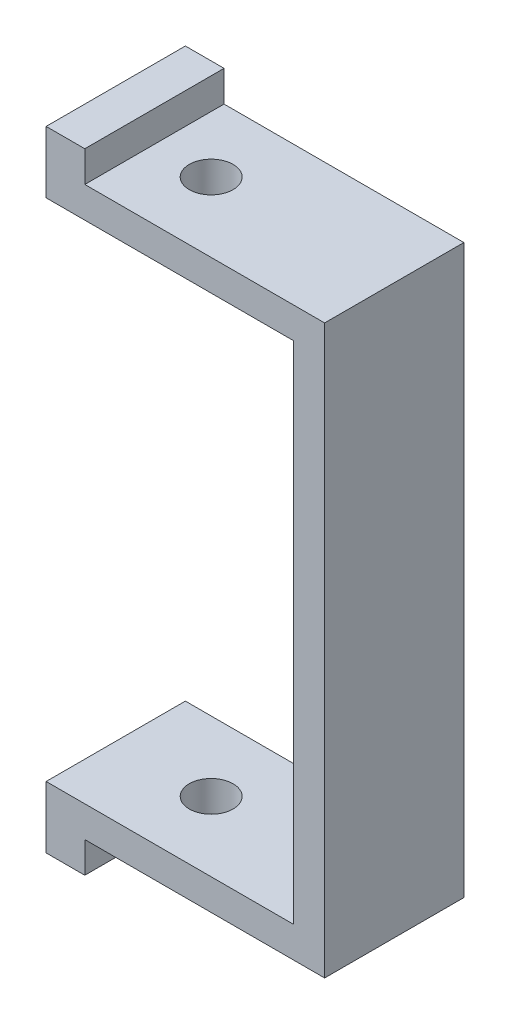
SolidWorks part; units mm, degrees
ref_plane "Alzado" through (0, 0, 0) normal (0, 0, 1) x (1, 0, 0)
ref_plane "Planta" through (0, 0, 0) normal (0, 1, 0) x (1, 0, 0)
ref_plane "Vista lateral" through (0, 0, 0) normal (1, 0, 0) x (0, 0, -1)
sketch "Croquis1" plane through (0, 0, 0) normal (0, 0, 1) x (1, 0, 0)
  line L0 (3.75, 0) -> (27, 0)
  line L1 (27, 0) -> (27, 55)
  line L2 (27, 55) -> (3.75, 55)
  line L3 (0, 3) -> (24, 3)
  line L4 (24, 3) -> (24, 52)
  line L5 (24, 52) -> (0, 52)
  line L6 (0, 55) -> (0, 52)
  line L7 (0, 3) -> (0, 0)
  line L10 (0, 0) -> (0, -3)
  line L11 (0, -3) -> (3.75, -3)
  line L12 (3.75, 0) -> (3.75, -3)
  line L14 (0, 55) -> (0, 58)
  line L15 (0, 58) -> (3.75, 58)
  line L16 (3.75, 55) -> (3.75, 58)
  line L17 (0, 0) -> (27, 0) construction
  line L18 (27, 55) -> (0, 55) construction
  dimension "D2" = 55
  dimension "D3" = 27
  dimension "D4" = 27
  dimension "D5" = 3
  dimension "D6" = 3
  dimension "D7" = 3.75
  dimension "D1" = 3
extrude "Saliente-Extruir1" add sketch "Croquis1" along normal blind 13.5
sketch "Croquis4" plane through (0, 0, 0) normal (0, -1, 0) x (1, 0, 0)
  line L0 (27, 13.5) -> (27, 0) construction
  line L1 (3.75, 13.5) -> (3.75, 0) construction
  circle A0 centre (9.25, 6.75) radius 2.125
  point P4 (27, 6.75)
  dimension "D1" = 4.25
  dimension "D2" = 5.5
extrude "Cortar-Extruir1" cut sketch "Croquis4" against normal blind 76
